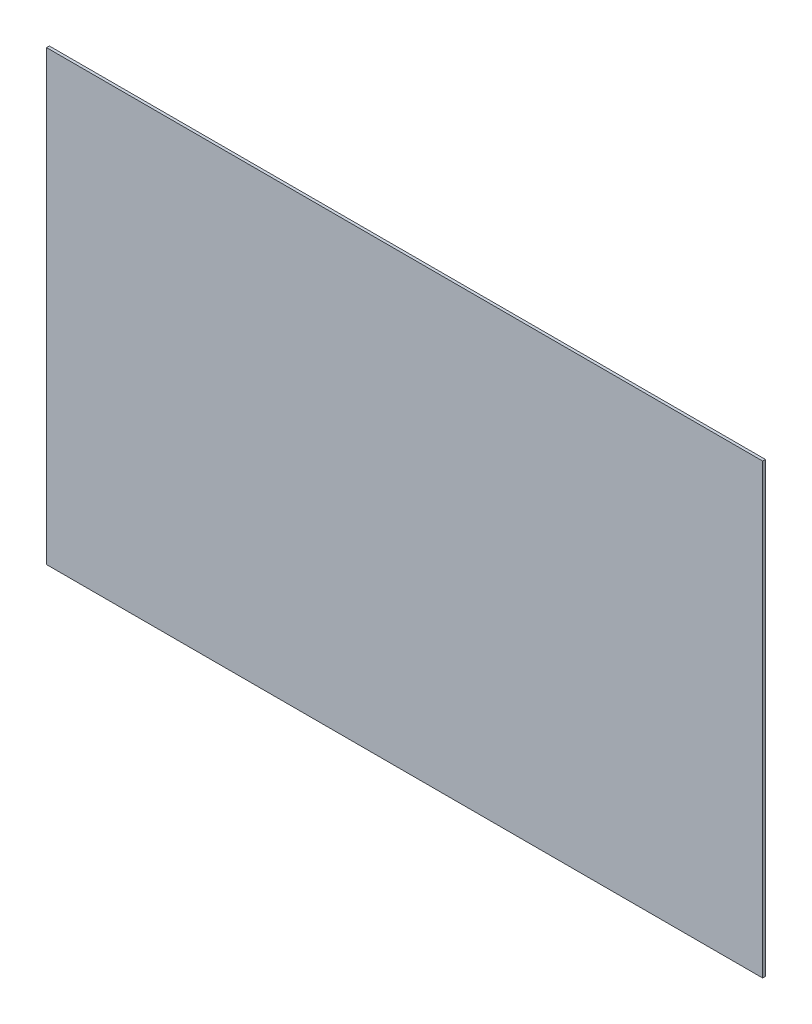
SolidWorks part; units mm, degrees
ref_plane "Front Plane" through (0, 0, 0) normal (0, 0, 1) x (1, 0, 0)
ref_plane "Top Plane" through (0, 0, 0) normal (0, 1, 0) x (1, 0, 0)
ref_plane "Right Plane" through (0, 0, 0) normal (1, 0, 0) x (0, 0, -1)
sketch "Sketch1" plane through (0, 0, 0) normal (0, 0, 1) x (1, 0, 0)
  line L1 (-406.4, -254.127) -> (406.4, -254.127)
  line L2 (-406.4, -254.127) -> (-406.4, 254.127)
  line L3 (-406.4, 254.127) -> (406.4, 254.127)
  line L4 (406.4, -254.127) -> (406.4, 254.127)
  line L5 (-406.4, -254.127) -> (406.4, 254.127) construction
  line L6 (-406.4, 254.127) -> (406.4, -254.127) construction
  point P0 (0, 0)
  dimension "D1" = 508.254
  dimension "D2" = 812.8
extrude "Boss-Extrude1" add sketch "Sketch1" along normal blind 3.175
